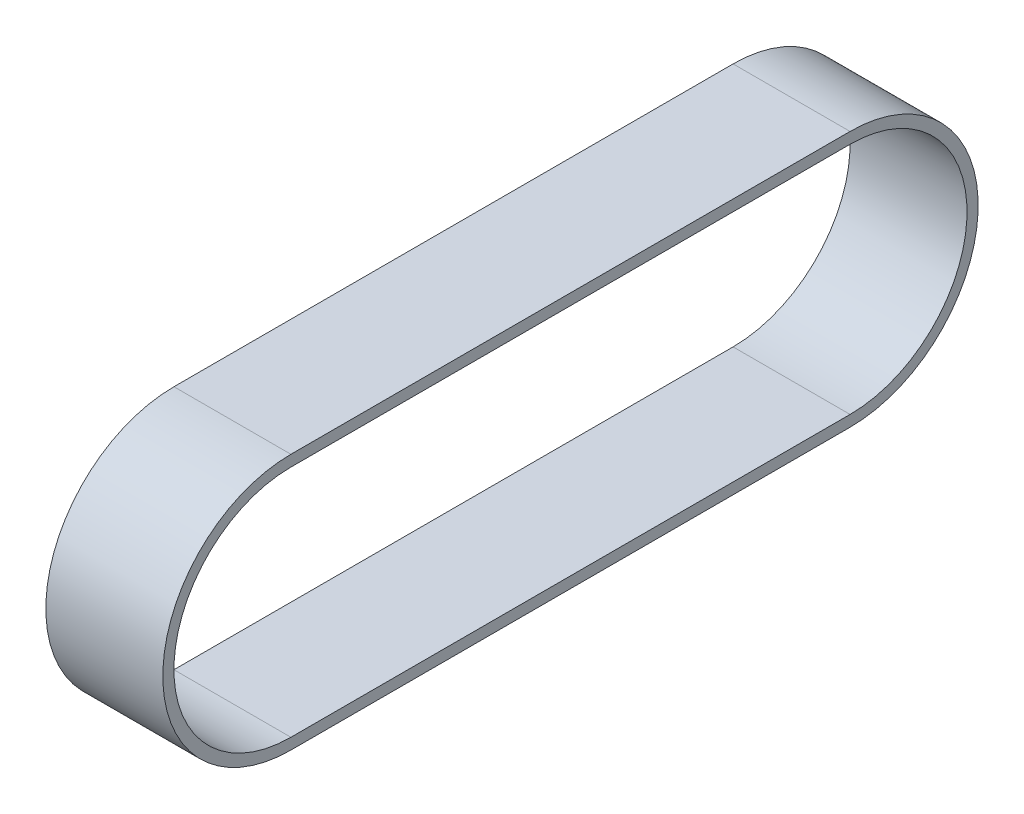
SolidWorks part; units mm, degrees
ref_plane "정면" through (0, 0, 0) normal (0, 0, 1) x (1, 0, 0)
ref_plane "윗면" through (0, 0, 0) normal (0, 1, 0) x (1, 0, 0)
ref_plane "우측면" through (0, 0, 0) normal (1, 0, 0) x (0, 0, -1)
sketch "스케치1" plane through (0, 0, 0) normal (1, 0, 0) x (0, 0, -1)
  line L0 (-41.946, 50) -> (197.054, 50)
  line L1 (-41.946, -50) -> (197.054, -50)
  line L2 (-41.946, 54.752) -> (197.054, 54.752)
  line L3 (-41.946, -54.752) -> (197.054, -54.752)
  arc A0 (-41.946, 50) -> (-41.946, -50) centre (-41.946, 0) ccw
  arc A1 (197.054, -50) -> (197.054, 50) centre (197.054, 0) ccw
  arc A2 (197.054, -54.752) -> (197.054, 54.752) centre (197.054, 0) ccw
  arc A3 (-41.946, 54.752) -> (-41.946, -54.752) centre (-41.946, 0) ccw
  dimension "D1" = 100
  dimension "D2" = 100
  dimension "D3" = 239
  dimension "D4" = 4.752
extrude "보스-돌출1" add sketch "스케치1" along normal blind 50
